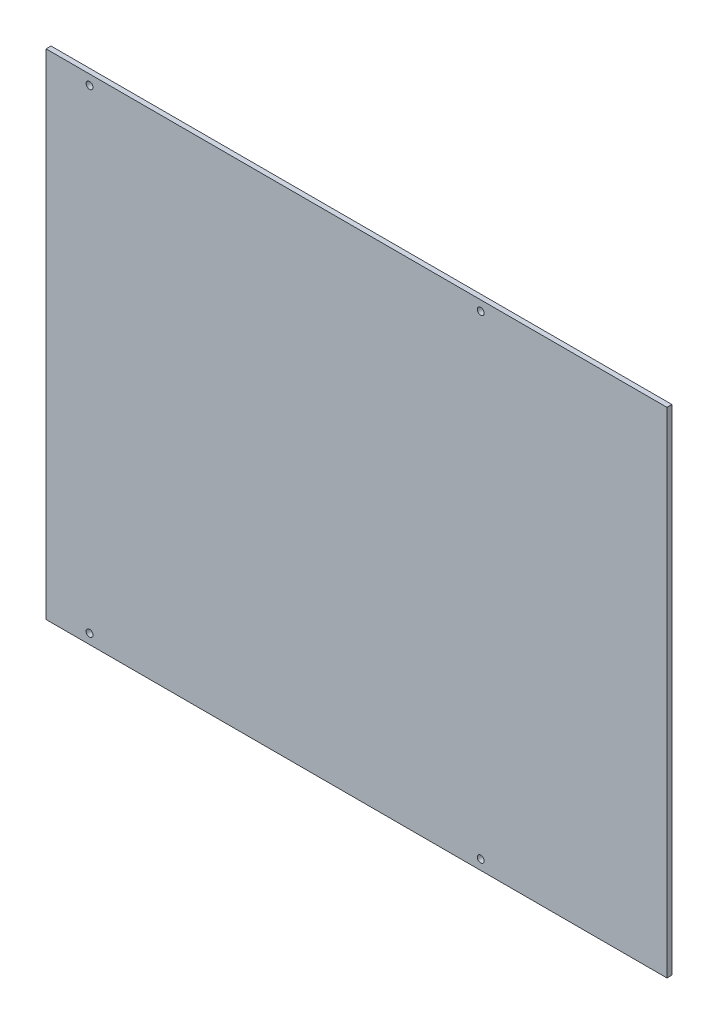
SolidWorks part; units mm, degrees
ref_plane "Plan de face" through (0, 0, 0) normal (0, 0, 1) x (1, 0, 0)
ref_plane "Plan de dessus" through (0, 0, 0) normal (0, 1, 0) x (1, 0, 0)
ref_plane "Plan de droite" through (0, 0, 0) normal (1, 0, 0) x (0, 0, -1)
sketch "Esquisse1" plane through (0, 0, 0) normal (0, 0, 1) x (1, 0, 0)
  line L1 (-250, -199) -> (250, -199)
  line L2 (-250, -199) -> (-250, 199)
  line L3 (-250, 199) -> (250, 199)
  line L4 (250, -199) -> (250, 199)
  line L5 (-250, -199) -> (250, 199) construction
  line L6 (-250, 199) -> (250, -199) construction
  point P0 (0, 0)
  dimension "D1" = 398
  dimension "D2" = 500
extrude "Boss.-Extru.1" add sketch "Esquisse1" along normal blind 4
sketch "Esquisse2" plane through (0, 0, 4) normal (0, 0, 1) x (1, 0, 0)
  line L0 (250, 199) -> (-250, 199) construction
  line L1 (-242, -191) -> (242, -191) construction
  line L2 (-242, -191) -> (-242, 191) construction
  line L3 (-242, 191) -> (242, 191) construction
  line L4 (242, -191) -> (242, 191) construction
  line L5 (-242, -191) -> (242, 191) construction
  line L6 (-242, 191) -> (242, -191) construction
  line L7 (-250, 199) -> (-250, -199) construction
  line L8 (250, -199) -> (250, 199) construction
  point P0 (100, 191)
  point P1 (-215, 191)
  point P2 (100, -191)
  point P3 (-215, -191)
  point P4 (0, 0)
  dimension "D1" = 8
  dimension "D2" = 8
  dimension "D3" = 35
  dimension "D4" = 150
hole_wizard "Dégagement M51" positions "Esquisse3D1" profile "Esquisse3" hole size "M5" standard "ISO" end condition through all
sketch3d "Esquisse3D1"
  point P0 (-215, 191, 4)
  point P3 (100, 191, 4)
  point P8 (100, -191, 4)
  point P11 (-215, -191, 4)
sketch "Esquisse3" plane through (-215, 191, 4) normal (1, 0, 0) x (0, -1, 0)
  line L0 (0, 0) -> (0, 4)
  line L1 (0, 4) -> (2.75, 4)
  line L2 (2.75, 4) -> (2.75, 0)
  line L5 (2.75, 0) -> (0, 0)
  line L11 (0, -6.35) -> (0, 107.95) construction
  dimension "Diamètre du perçage jusqu'au prochain" = 5.5
  dimension "Profondeur du perçage jusqu'au prochain" = 4
